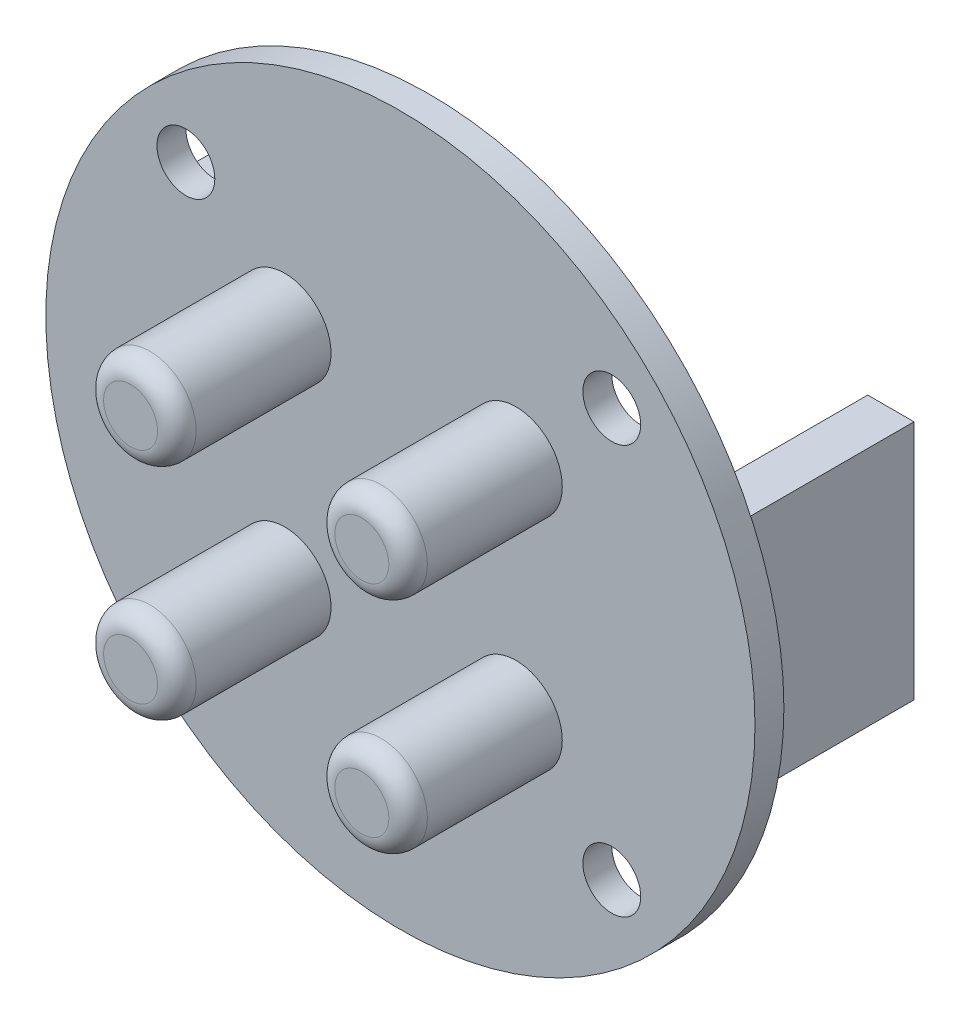
SolidWorks part; units mm, degrees
ref_plane "Plan de face" through (0, 0, 0) normal (0, 0, 1) x (1, 0, 0)
ref_plane "Plan de dessus" through (0, 0, 0) normal (0, 1, 0) x (1, 0, 0)
ref_plane "Plan de droite" through (0, 0, 0) normal (1, 0, 0) x (0, 0, -1)
sketch "Esquisse1" plane through (0, 0, 0) normal (0, 0, 1) x (1, 0, 0)
  circle A0 centre (0, 0) radius 18.4
  dimension "D1" = 36.8
extrude "Boss.-Extru.1" add sketch "Esquisse1" along normal blind 1.5
sketch "Esquisse3" plane through (0, 0, 0) normal (0, 0, -1) x (-1, 0, 0)
  line L0 (5.9331, 46.0783) -> (28.0331, 46.0783) construction
  line L1 (28.0331, 46.0783) -> (28.0331, 24.8783) construction
  line L2 (28.0331, 24.8783) -> (5.9331, 24.8783) construction
  line L3 (5.9331, 24.8783) -> (5.9331, 46.0783) construction
  line L4 (0, 0) -> (11.1309, -10.6776) construction
  line L5 (0, 0) -> (-10.9691, 10.5224) construction
  line L6 (11.1309, 10.5224) -> (-10.9691, -10.6776) construction
  line L7 (11.1309, 10.5224) -> (-10.9691, 10.5224) construction
  line L8 (-10.9691, 10.5224) -> (-10.9691, -10.6776) construction
  line L9 (-10.9691, -10.6776) -> (11.1309, -10.6776) construction
  line L10 (11.1309, -10.6776) -> (11.1309, 10.5224) construction
  circle A0 centre (28.0331, 46.0783) radius 1.5
  circle A1 centre (28.0331, 24.8783) radius 1.5
  circle A2 centre (5.9331, 24.8783) radius 1.5
  circle A3 centre (5.9331, 46.0783) radius 1.5
  circle A4 centre (11.1309, 10.5224) radius 1.5
  circle A5 centre (0, 0) radius 18.4 construction
  circle A6 centre (11.1309, -10.6776) radius 1.5
  circle A7 centre (-10.9691, -10.6776) radius 1.5
  circle A8 centre (-10.9691, 10.5224) radius 1.5
  point P8 (1.5011, 18.3387)
  point P17 (0, 0)
  point P22 (-1.7683, 18.3148)
  point P23 (-1.7683, 18.3148)
  point P24 (1.5011, 18.3387)
  dimension "D3" = 3
  dimension "D4" = 3
  dimension "D5" = 3
  dimension "D6" = 3
  dimension "D9" = 3
  dimension "D10" = 3
  dimension "D11" = 3
  dimension "D12" = 3
  dimension "D1" = 21.2
  dimension "D2" = 22.1
  dimension "D7" = 30.6243
  dimension "D8" = 22.1
extrude "Enlèv. mat.-Extru.1" cut sketch "Esquisse3" against normal blind 10
sketch "Esquisse4" plane through (0, 0, 0) normal (0, 0, -1) x (-1, 0, 0)
  line L1 (12.75, 6.25) -> (15.15, 6.25)
  line L2 (12.75, 6.25) -> (12.75, -6.25)
  line L3 (12.75, -6.25) -> (15.15, -6.25)
  line L4 (15.15, 6.25) -> (15.15, -6.25)
  line L5 (-15.15, 6.25) -> (-12.75, 6.25)
  line L6 (-15.15, 6.25) -> (-15.15, -6.25)
  line L7 (-15.15, -6.25) -> (-12.75, -6.25)
  line L8 (-12.75, 6.25) -> (-12.75, -6.25)
  circle A0 centre (0, 0) radius 18.4 construction
  dimension "D1" = 12.5
  dimension "D2" = 12.5
  dimension "D3" = 6.25
  dimension "D4" = 30.3
  dimension "D5" = 2.4
  dimension "D6" = 2.4
  dimension "D7" = 6.25
extrude "Boss.-Extru.2" add sketch "Esquisse4" along normal blind 10
sketch "Esquisse5" plane through (0, 0, 1.5) normal (0, 0, 1) x (1, 0, 0)
  line L1 (-8.4, 8.1) -> (8.4, 8.1) construction
  line L2 (-8.4, 8.1) -> (-8.4, -8.1) construction
  line L3 (-8.4, -8.1) -> (8.4, -8.1) construction
  line L4 (8.4, 8.1) -> (8.4, -8.1) construction
  line L5 (-6, 5.7) -> (6, 5.7) construction
  line L6 (-6, 5.7) -> (-6, -5.7) construction
  line L7 (-6, -5.7) -> (6, -5.7) construction
  line L8 (6, 5.7) -> (6, -5.7) construction
  circle A0 centre (6, 5.7) radius 2.4
  circle A1 centre (6, -5.7) radius 2.4
  circle A2 centre (-6, -5.7) radius 2.4
  circle A3 centre (-6, 5.7) radius 2.4
  circle A4 centre (0, 0) radius 18.4 construction
  point P12 (0, 0)
  dimension "D1" = 16.8
  dimension "D2" = 16.2
  dimension "D3" = 2.4
  dimension "D4" = 2.4
  dimension "D5" = 2.4
  dimension "D6" = 2.4
  dimension "D7" = 8.1
  dimension "D8" = 8.4
extrude "Boss.-Extru.3" add sketch "Esquisse5" along normal blind 8
fillet "Congé1" radius 1 4 edges at (8.4, 5.7, 9.5) (8.4, -5.7, 9.5) (-3.6, -5.7, 9.5) (-3.6, 5.7, 9.5)
